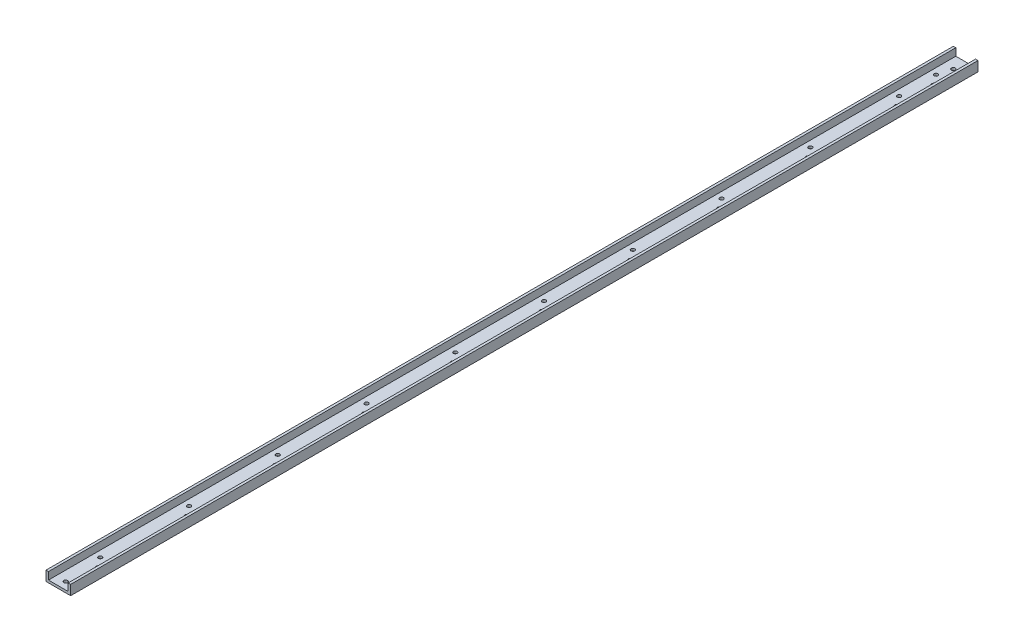
SolidWorks part; units mm, degrees
ref_plane "Front Plane" through (0, 0, 0) normal (0, 0, 1) x (1, 0, 0)
ref_plane "Top Plane" through (0, 0, 0) normal (0, 1, 0) x (1, 0, 0)
ref_plane "Right Plane" through (0, 0, 0) normal (1, 0, 0) x (0, 0, -1)
sketch "Sketch1" plane through (0, 0, 0) normal (0, 0, 1) x (1, 0, 0)
  line L0 (3.175, 3.175) -> (3.175, 12.7)
  line L1 (0, 0) -> (31.75, 0)
  line L2 (0, 0) -> (0, 12.7)
  line L4 (31.75, 0) -> (31.75, 12.7)
  line L5 (3.175, 3.175) -> (28.575, 3.175)
  line L6 (28.575, 3.175) -> (28.575, 12.7)
  line L7 (0, 12.7) -> (3.175, 12.7)
  line L8 (31.75, 12.7) -> (28.575, 12.7)
  dimension "D1" = 31.75
  dimension "D2" = 12.7
  dimension "D3" = 3.175
extrude "Boss-Extrude1" add sketch "Sketch1" along normal blind 1168.4
sketch "Sketch3" plane through (0, 3.175, 0) normal (0, 1, 0) x (1, 0, 0)
  line L0 (11.1125, -1109.6625) -> (11.1125, -1122.3625) construction
  line L1 (11.1125, -1122.3625) -> (20.6375, -1122.3625) construction
  line L2 (20.6375, -1122.3625) -> (11.1125, -1109.6625) construction
  line L3 (20.6375, -1122.3625) -> (20.6375, -1168.4) construction
  line L4 (28.575, -1168.4) -> (3.175, -1168.4) construction
  circle A1 centre (11.1125, -1109.6625) radius 2.413
  circle A3 centre (20.6375, -1122.3625) radius 2.413
  dimension "D1" = 9.525
  dimension "D2" = 12.7
  dimension "D3" = 46.0375
extrude "Cut-Extrude1" cut sketch "Sketch3" against normal up to next
sketch "Sketch4" plane through (0, 3.175, 0) normal (0, 1, 0) x (1, 0, 0)
  line L0 (15.875, -1168.4) -> (15.875, -1158.875) construction
  line L1 (28.575, -1168.4) -> (3.175, -1168.4) construction
  circle A0 centre (15.875, -1158.875) radius 2.413
  dimension "D2" = 4.826
  dimension "D1" = 9.525
extrude "Cut-Extrude2" cut sketch "Sketch4" against normal up to next
pattern_linear "LPattern1" count 10 spacing 114.3 along (0, 0, -1) of "Cut-Extrude1"
sketch "Sketch5" plane through (0, 3.175, 0) normal (0, 1, 0) x (1, 0, 0)
  circle A0 centre (20.6375, -46.0375) radius 2.413 construction
  circle A1 centre (20.6375, -46.0375) radius 2.413
  circle A2 centre (11.1125, -33.3375) radius 2.413 construction
  circle A3 centre (11.1125, -33.3375) radius 2.413
  circle A4 centre (-236.5375, -33.3375) radius 2.413 construction
  circle A5 centre (-236.5375, -33.3375) radius 2.413
  circle A6 centre (-227.0125, -46.0375) radius 2.413 construction
  circle A7 centre (-227.0125, -46.0375) radius 2.413
extrude "Cut-Extrude3" cut sketch "Sketch5" against normal through all
sketch "Sketch6" plane through (0, 3.175, 0) normal (0, 1, 0) x (1, 0, 0)
  line L0 (15.875, 0) -> (15.875, -15.875) construction
  line L1 (28.575, 0) -> (3.175, 0) construction
  circle A0 centre (15.875, -15.875) radius 2.413
  dimension "D2" = 4.826
  dimension "D1" = 15.875
extrude "Cut-Extrude4" cut sketch "Sketch6" against normal up to next
